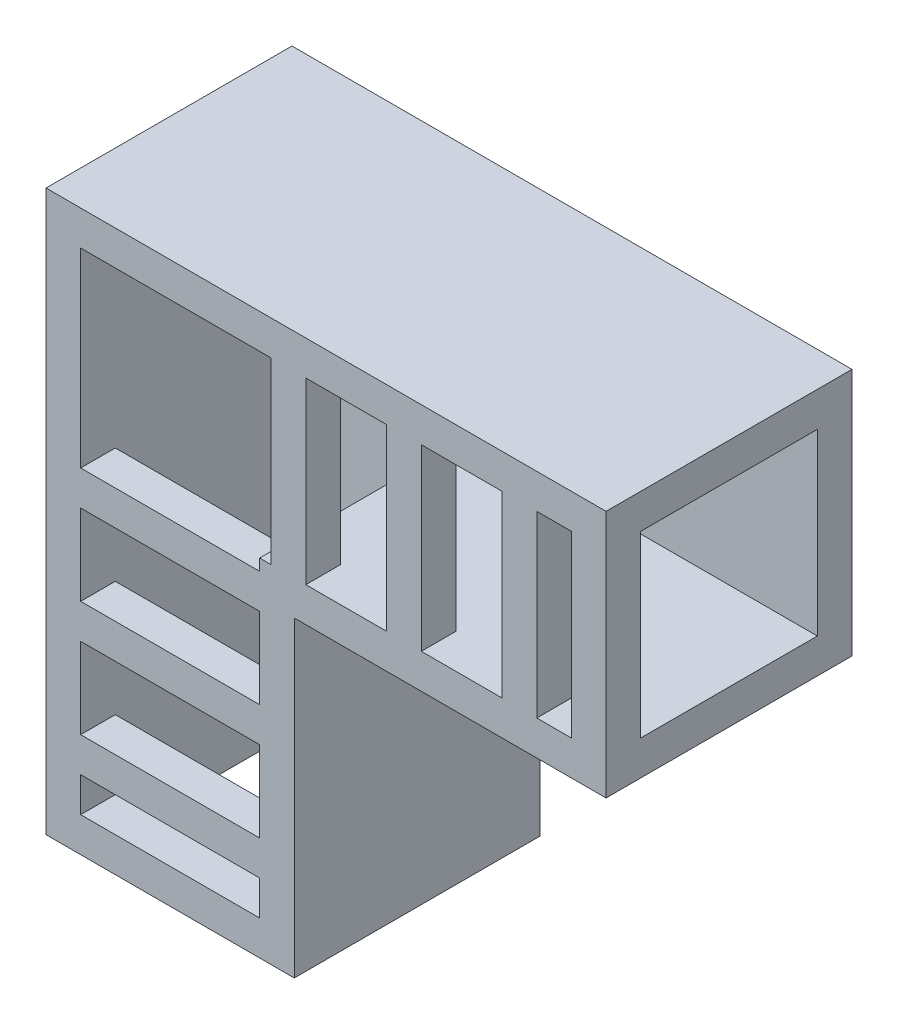
SolidWorks part; units mm, degrees
material "ABS"
ref_plane "Front Plane" through (0, 0, 0) normal (0, 0, 1) x (1, 0, 0)
ref_plane "Top Plane" through (0, 0, 0) normal (0, 1, 0) x (1, 0, 0)
ref_plane "Right Plane" through (0, 0, 0) normal (1, 0, 0) x (0, 0, -1)
sketch "Sketch1" plane through (0, 0, 0) normal (0, 0, 1) x (1, 0, 0)
  line L0 (0, 0) -> (15.5, 0)
  line L1 (15.5, 0) -> (15.5, 30)
  line L2 (15.5, 30) -> (45.5, 30)
  line L3 (45.5, 30) -> (45.5, 45.5)
  line L4 (45.5, 45.5) -> (0, 45.5)
  line L5 (0, 45.5) -> (0, 0)
  dimension "D1" = 15.5
  dimension "D2" = 15.5
  dimension "D3" = 30
  dimension "D4" = 30
extrude "Boss-Extrude1" add sketch "Sketch1" along normal blind 15.3
shell "Shell1" thickness 3
sketch "Sketch2" plane through (0, 0, 18.3) normal (0, 0, 1) x (1, 0, 0)
  line L0 (29.5, 30) -> (29.5, 45.5)
  line L1 (26.5, 45.5) -> (26.5, 30)
  line L2 (19.5, 30) -> (19.5, 45.5)
  line L3 (16.5, 45.5) -> (16.5, 30)
  line L12 (15.5, 6) -> (0, 6)
  line L13 (15.5, 9) -> (0, 9)
  line L14 (15.5, 19) -> (0, 19)
  line L15 (15.5, 16) -> (0, 16)
  line L16 (15.5, 29) -> (0, 29)
  line L17 (15.5, 26) -> (0, 26)
  line L18 (0, 45.5) -> (0, 3)
  line L19 (0, 3) -> (15.5, 3)
  line L20 (15.5, 3) -> (15.5, 30)
  line L21 (15.5, 30) -> (42.5, 30)
  line L22 (42.5, 30) -> (42.5, 45.5)
  line L23 (42.5, 45.5) -> (0, 45.5)
  line L24 (0, 45.5) -> (0, 3)
  line L25 (0, 3) -> (15.5, 3)
  line L26 (15.5, 3) -> (15.5, 30)
  line L27 (15.5, 30) -> (42.5, 30)
  line L28 (42.5, 30) -> (42.5, 45.5)
  line L29 (42.5, 45.5) -> (0, 45.5)
  line L30 (39.5, 30) -> (39.5, 45.5)
  line L31 (39.5, 45.5) -> (36.5, 45.5)
  line L32 (36.5, 45.5) -> (36.5, 30)
  dimension "D2" = 3
  dimension "D4" = 3
  dimension "D5" = 3
  dimension "D6" = 3
  dimension "D1" = 3
  dimension "D3" = 3
  dimension "D7" = 3
extrude "Cut-Extrude1" cut sketch "Sketch2" against normal blind 5 contours L3 L29 L24 L16 L26 L27 | L1 L29 L2 L27 | L32 L29 L0 L27 | L30 L27 L28 L29 | L14 L26 L17 L24 | L13 L26 L15 L24 | L25 L26 L12 L24
